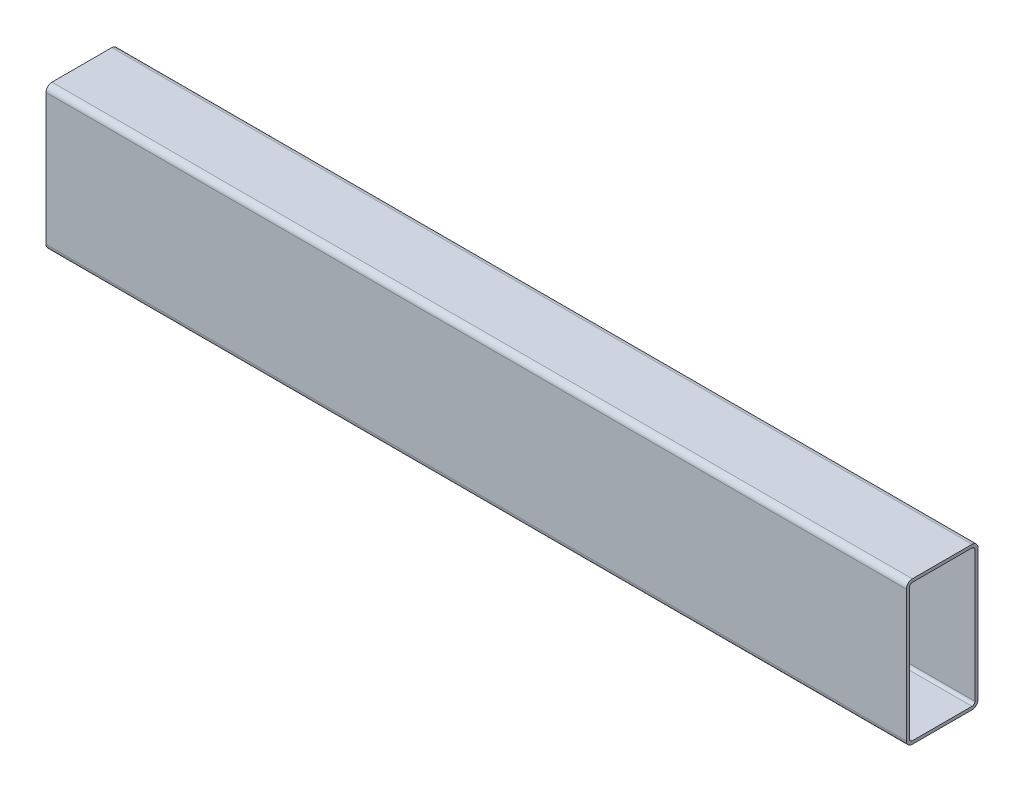
SolidWorks part; units mm, degrees
material "Plain Carbon Steel"
ref_plane "Front Plane" through (0, 0, 0) normal (0, 0, 1) x (1, 0, 0)
ref_plane "Top Plane" through (0, 0, 0) normal (0, 1, 0) x (1, 0, 0)
ref_plane "Right Plane" through (0, 0, 0) normal (1, 0, 0) x (0, 0, -1)
sketch "Sketch1" plane through (0, 0, 0) normal (1, 0, 0) x (0, 0, -1)
  line L1 (-9.4971, -10.2658) -> (22.2529, -10.2658)
  line L2 (-12.6721, -7.0908) -> (-12.6721, 62.7592)
  line L3 (-9.4971, 65.9342) -> (22.2529, 65.9342)
  line L4 (25.4279, -7.0908) -> (25.4279, 62.7592)
  arc A0 (-12.6721, 62.7592) -> (-9.4971, 65.9342) centre (-9.4971, 62.7592) cw
  arc A1 (-12.6721, -7.0908) -> (-9.4971, -10.2658) centre (-9.4971, -7.0908) ccw
  arc A2 (22.2529, -10.2658) -> (25.4279, -7.0908) centre (22.2529, -7.0908) ccw
  arc A3 (25.4279, 62.7592) -> (22.2529, 65.9342) centre (22.2529, 62.7592) ccw
  point P6 (-12.6721, 65.9342)
  point P11 (25.4279, -10.2658)
  point P14 (25.4279, 65.9342)
  dimension "D3" = 3.175
  dimension "D1" = 76.2
  dimension "D2" = 38.1
extrude "Extrude-Thin2" add sketch "Sketch1" along normal blind 457.2 thin contours L2 A0 L3 A3 L4 A2 L1 A1 thin type one direction reverse wall 1.651
